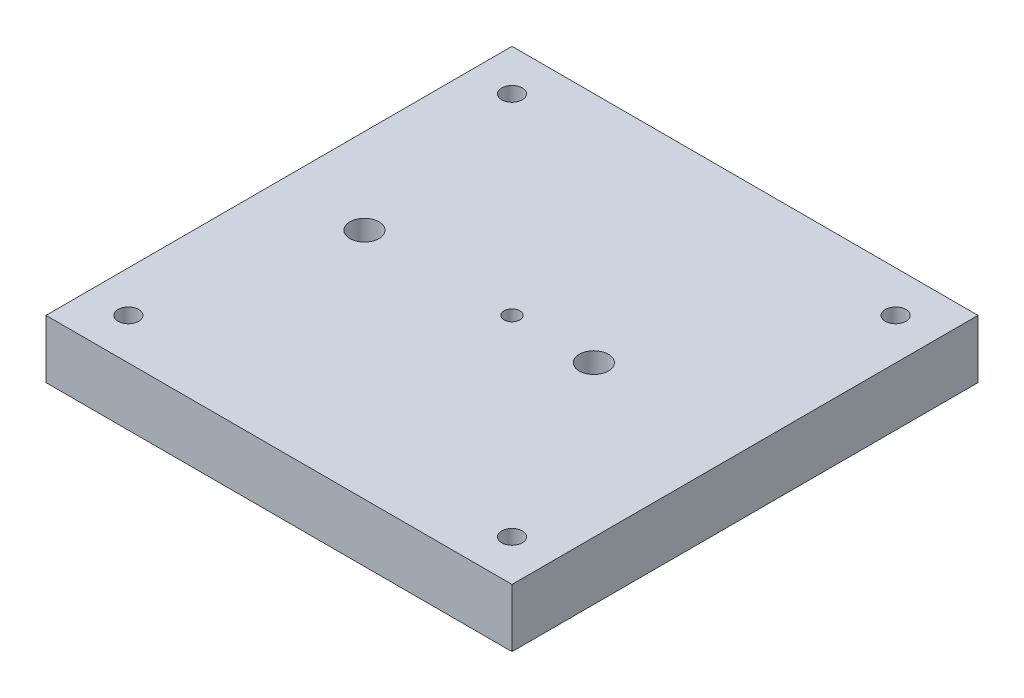
SolidWorks part; units mm, degrees
ref_plane "Front Plane" through (0, 0, 0) normal (0, 0, 1) x (1, 0, 0)
ref_plane "Top Plane" through (0, 0, 0) normal (0, 1, 0) x (1, 0, 0)
ref_plane "Right Plane" through (0, 0, 0) normal (1, 0, 0) x (0, 0, -1)
sketch "Sketch1" plane through (0, 0, 0) normal (0, 1, 0) x (1, 0, 0)
  line L1 (-50.8, 50.8) -> (50.8, 50.8)
  line L2 (-50.8, 50.8) -> (-50.8, -50.8)
  line L3 (-50.8, -50.8) -> (50.8, -50.8)
  line L4 (50.8, 50.8) -> (50.8, -50.8)
  line L5 (-50.8, 50.8) -> (50.8, -50.8) construction
  line L6 (-50.8, -50.8) -> (50.8, 50.8) construction
  point P0 (0, 0)
  point P6 (0, 0)
  dimension "D1" = 101.6
  dimension "D2" = 101.6
extrude "Boss-Extrude1" add sketch "Sketch1" against normal blind 12.7
sketch "Projection of Holes" plane through (0, 0, 0) normal (0, 1, 0) x (1, 0, 0)
  line L4 (50.8, -50.8) -> (50.8, 50.8)
  line L5 (50.8, 50.8) -> (-50.8, 50.8)
  line L6 (-50.8, 50.8) -> (-50.8, -50.8)
  line L7 (-50.8, -50.8) -> (50.8, -50.8)
  line L8 (50.8, -50.8) -> (50.8, 50.8)
  line L9 (50.8, 50.8) -> (-50.8, 50.8)
  line L10 (-50.8, 50.8) -> (-50.8, -50.8)
  line L11 (-50.8, -50.8) -> (50.8, -50.8)
  ellipse E2 centre (17.8436, 0) end of major axis (17.8436, 3.175) minor radius 3.1739
  ellipse E3 centre (-32.1651, 0) end of major axis (-32.1651, 5.9817) minor radius 5.9797
  dimension "D2" = 17.8436
  dimension "D3" = 32.1651
  dimension "D1" = 0
sketch "Sketch3" plane through (0, 0, 0) normal (0, 1, 0) x (1, 0, 0)
  line L0 (-50.8, 50.8) -> (50.8, -50.8) construction
  circle A0 centre (17.8436, 0) radius 3.175
  circle A1 centre (-32.1651, 0) radius 3.175
  circle A2 centre (-41.8197, 41.8197) radius 2.2479
  circle A3 centre (0, 0) radius 10.1224 construction
  circle A4 centre (41.8197, 41.8197) radius 2.2479
  circle A5 centre (41.8197, -41.8197) radius 2.2479
  circle A6 centre (-41.8197, -41.8197) radius 2.2479
  circle A7 centre (0, 0) radius 1.7272
  point P22 (0, 0)
  dimension "D1" = 6.35
  dimension "D2" = 6.35
  dimension "D3" = 4.4958
  dimension "D6" = 3.4544
  dimension "D4" = 12.7
  dimension "D5" = 4
extrude "Cut-Extrude1" cut sketch "Sketch3" against normal through all
